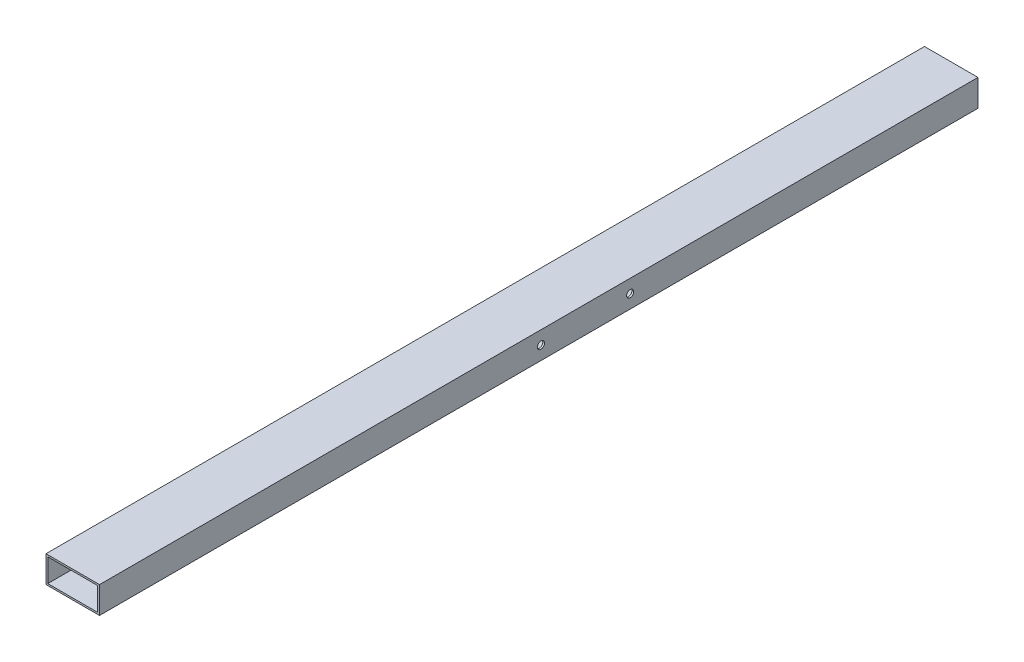
SolidWorks part; units mm, degrees
ref_plane "Front Plane" through (0, 0, 0) normal (0, 0, 1) x (1, 0, 0)
ref_plane "Top Plane" through (0, 0, 0) normal (0, 1, 0) x (1, 0, 0)
ref_plane "Right Plane" through (0, 0, 0) normal (1, 0, 0) x (0, 0, -1)
sketch "Croquis1" plane through (0, 0, 0) normal (0, 0, 1) x (1, 0, 0)
  line L1 (-30, -15) -> (30, -15)
  line L2 (-30, -15) -> (-30, 15)
  line L3 (-30, 15) -> (30, 15)
  line L4 (30, -15) -> (30, 15)
  line L5 (-30, -15) -> (30, 15) construction
  line L6 (-30, 15) -> (30, -15) construction
  line L7 (-28, -13) -> (28, -13)
  line L8 (-28, -13) -> (-28, 13)
  line L9 (-28, 13) -> (28, 13)
  line L10 (28, -13) -> (28, 13)
  line L11 (-28, -13) -> (28, 13) construction
  line L12 (-28, 13) -> (28, -13) construction
  point P0 (0, 0)
  point P6 (0, 0)
  dimension "D1" = 60
  dimension "D2" = 30
  dimension "D3" = 2
  dimension "D4" = 2
extrude "Saliente-Extruir1" add sketch "Croquis1" along normal blind 985
sketch "Croquis2" plane through (30, 0, 0) normal (1, 0, 0) x (0, 0, -1)
  line L0 (-300, 15) -> (-300, -15) construction
  line L1 (-985, 15) -> (0, 15) construction
  line L2 (-985, -15) -> (0, -15) construction
  line L3 (0, -15) -> (0, 15) construction
  line L4 (-985, 0) -> (0, 0) construction
  line L5 (-985, -15) -> (-985, 15) construction
  circle A0 centre (-390, 0) radius 4
  circle A1 centre (-490, 0) radius 4
  dimension "D2" = 8
  dimension "D1" = 300
  dimension "D3" = 90
  dimension "D4" = 100
extrude "Cortar-Extruir1" cut sketch "Croquis2" against normal through all
